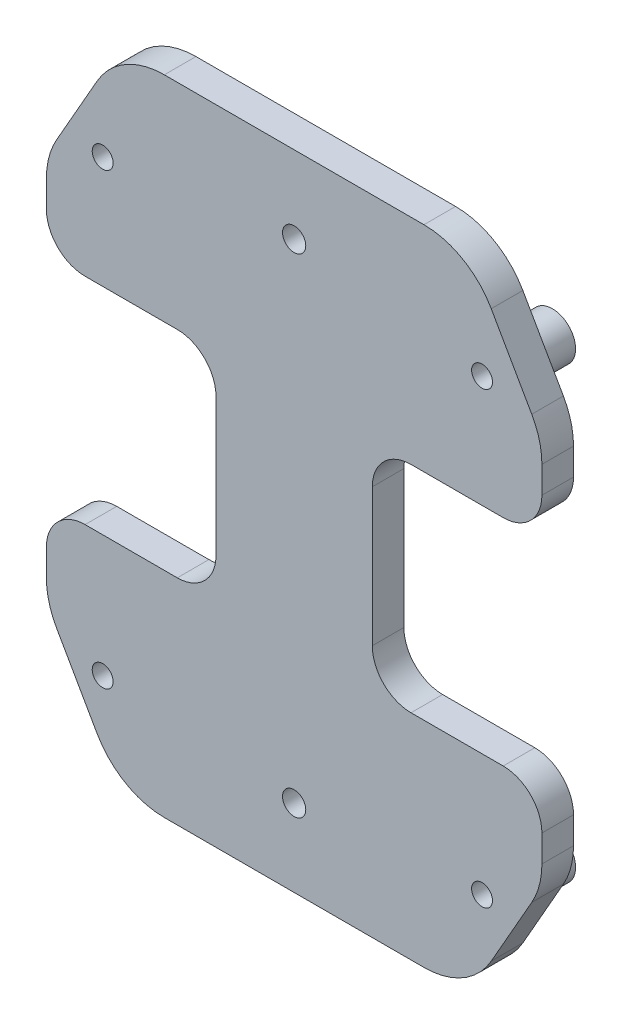
SolidWorks part; units mm, degrees
ref_plane "Ön Düzlem" through (0, 0, 0) normal (0, 0, 1) x (1, 0, 0)
ref_plane "Üst Düzlem" through (0, 0, 0) normal (0, 1, 0) x (1, 0, 0)
ref_plane "Sağ Düzlem" through (0, 0, 0) normal (1, 0, 0) x (0, 0, -1)
sketch "Çizim1" plane through (0, 0, 0) normal (0, 0, 1) x (1, 0, 0)
  line L12 (-26.9423, 14.7698) -> (-15.0365, 14.7698)
  line L13 (-46.9741, 0.8817) -> (-14.6226, 0.8817) construction
  line L14 (-25.3981, 37.3713) -> (-30.6317, 28.1828)
  line L15 (-31.9423, 23.2336) -> (-31.9423, 19.7698)
  line L16 (-26.9423, -13.0064) -> (-15.0365, -13.0064)
  line L17 (0.0577, 32.422) -> (0.0577, 69.5498) construction
  line L18 (-16.7087, 42.422) -> (16.8241, 42.422)
  line L19 (-16.7087, -40.6586) -> (16.8241, -40.6586)
  line L20 (-25.3981, -35.6078) -> (-30.6317, -26.4194)
  line L21 (25.5134, -35.6078) -> (30.747, -26.4194)
  line L22 (32.0577, 23.2336) -> (32.0577, 19.7698)
  line L23 (25.5134, 37.3713) -> (30.747, 28.1828)
  line L24 (27.0577, -13.0064) -> (15.1518, -13.0064)
  line L25 (27.0577, 14.7698) -> (15.1518, 14.7698)
  line L26 (-10.0365, 9.7698) -> (-10.0365, -8.0064)
  line L27 (10.1518, 9.7698) -> (10.1518, -8.0064)
  line L28 (32.0577, -18.0064) -> (32.0577, -21.4701)
  line L29 (-31.9423, -18.0064) -> (-31.9423, -21.4701)
  circle A0 centre (20.2843, 32.422) radius 1.5
  circle A1 centre (-20.1689, 32.422) radius 1.5
  circle A2 centre (-20.1689, -30.6586) radius 1.5
  circle A3 centre (20.2843, -30.6586) radius 1.5
  circle A16 centre (22.0577, -21.1183) radius 1.275
  circle A17 centre (-21.9423, -21.1183) radius 1.275
  circle A18 centre (22.0577, 22.8817) radius 1.275
  circle A19 centre (-21.9423, 22.8817) radius 1.275
  arc A20 (-30.6317, 28.1828) -> (-31.9423, 23.2336) centre (-21.9423, 23.2336) ccw
  arc A21 (-25.3981, 37.3713) -> (-16.7087, 42.422) centre (-16.7087, 32.422) cw
  arc A22 (-25.3981, -35.6078) -> (-16.7087, -40.6586) centre (-16.7087, -30.6586) ccw
  arc A23 (-30.6317, -26.4194) -> (-31.9423, -21.4701) centre (-21.9423, -21.4701) cw
  arc A24 (30.747, -26.4194) -> (32.0577, -21.4701) centre (22.0577, -21.4701) ccw
  arc A25 (25.5134, -35.6078) -> (16.8241, -40.6586) centre (16.8241, -30.6586) cw
  arc A26 (25.5134, 37.3713) -> (16.8241, 42.422) centre (16.8241, 32.422) ccw
  arc A27 (30.747, 28.1828) -> (32.0577, 23.2336) centre (22.0577, 23.2336) cw
  arc A28 (32.0577, -18.0064) -> (27.0577, -13.0064) centre (27.0577, -18.0064) ccw
  arc A29 (-26.9423, -13.0064) -> (-31.9423, -18.0064) centre (-26.9423, -18.0064) ccw
  arc A30 (15.1518, -13.0064) -> (10.1518, -8.0064) centre (15.1518, -8.0064) cw
  arc A31 (-10.0365, -8.0064) -> (-15.0365, -13.0064) centre (-15.0365, -8.0064) cw
  arc A32 (27.0577, 14.7698) -> (32.0577, 19.7698) centre (27.0577, 19.7698) ccw
  arc A33 (15.1518, 14.7698) -> (10.1518, 9.7698) centre (15.1518, 9.7698) ccw
  arc A34 (-15.0365, 14.7698) -> (-10.0365, 9.7698) centre (-15.0365, 9.7698) cw
  arc A35 (-31.9423, 19.7698) -> (-26.9423, 14.7698) centre (-26.9423, 19.7698) ccw
  circle A36 centre (0.0577, 32.422) radius 1.5
  circle A37 centre (0.0577, -30.6586) radius 1.5
  point P16 (32.0577, 0.8817)
  point P26 (0.0577, 42.422)
  point P27 (-31.9423, 0.8817)
  point P40 (0.0577, -40.6586)
  point P53 (32.0577, -13.0064)
  point P56 (-31.9423, -13.0064)
  point P64 (10.1518, -13.0064)
  point P67 (-10.0365, -13.0064)
  point P70 (32.0577, 14.7698)
  point P73 (10.1518, 14.7698)
  point P76 (-10.0365, 14.7698)
  point P79 (-31.9423, 14.7698)
  dimension "D1" = 10
  dimension "D2" = 5
extrude "Yükseklik-Ekstrüzyon1" add sketch "Çizim1" along normal blind 8
sketch "Çizim2" plane through (0, 0, 0) normal (0, 0, -1) x (-1, 0, 0)
  circle A0 centre (-22.0577, 22.8817) radius 4
  circle A1 centre (21.9423, 22.8817) radius 4
  circle A2 centre (-22.0577, -21.1183) radius 4
  circle A3 centre (21.9423, -21.1183) radius 4
  circle A4 centre (-0.0577, 32.422) radius 4
  circle A5 centre (-0.0577, -30.6586) radius 4
  dimension "D1" = 8
extrude "Kes-Ekstrüzyon1" cut sketch "Çizim2" against normal blind 5
sketch "Çizim3" plane through (0, 0, 8) normal (0, 0, 1) x (1, 0, 0)
  circle A0 centre (-20.1689, 32.422) radius 3.5
  circle A1 centre (20.2843, 32.422) radius 3.5
  circle A2 centre (20.2843, -30.6586) radius 3.5
  circle A3 centre (-20.1689, -30.6586) radius 3.5
  dimension "D1" = 7
extrude "Kes-Ekstrüzyon2" cut sketch "Çizim3" against normal blind 5
sketch "Çizim5" plane through (0, 0, 8) normal (0, 0, 1) x (1, 0, 0)
  line L0 (-10.0365, 0.8817) -> (-29.4082, 0.8817) construction
  line L1 (-5.8592, 35.2656) -> (5.9745, 35.2656)
  line L2 (-5.8592, 35.2656) -> (-5.8592, 29.5785)
  line L3 (-5.8592, 29.5785) -> (5.9745, 29.5785)
  line L4 (5.9745, 35.2656) -> (5.9745, 29.5785)
  line L5 (-5.8592, 35.2656) -> (5.9745, 29.5785) construction
  line L6 (-5.8592, 29.5785) -> (5.9745, 35.2656) construction
  line L7 (-10.0365, 9.7698) -> (-10.0365, -8.0064) construction
  line L8 (-5.8592, -27.815) -> (5.9745, -33.5021) construction
  line L9 (-5.8592, -33.5021) -> (5.9745, -27.815) construction
  line L10 (5.9745, -33.5021) -> (5.9745, -27.815)
  line L11 (-5.8592, -27.815) -> (5.9745, -27.815)
  line L12 (-5.8592, -33.5021) -> (-5.8592, -27.815)
  line L13 (-5.8592, -33.5021) -> (5.9745, -33.5021)
  point P0 (0.0577, 32.422)
  point P14 (0.0577, -30.6586)
extrude "Yükseklik-Ekstrüzyon2" add sketch "Çizim5" along normal blind 55
sketch "Çizim6" plane through (0, 0, 8) normal (0, 0, -1) x (-1, 0, 0)
  circle A0 centre (-0.0577, 32.422) radius 1.5 construction
  circle A1 centre (-0.0577, -30.6586) radius 1.5
  circle A2 centre (-0.0577, -30.6586) radius 1.5
  circle A3 centre (-0.0577, 32.422) radius 1.5
  dimension "D1" = 0
extrude "Kes-Ekstrüzyon3" cut sketch "Çizim6" against normal blind 70
sketch "Çizim7" plane through (0, 0, 63) normal (0, 0, 1) x (1, 0, 0)
  line L16 (-31.9423, 23.2336) -> (-31.9423, 19.7698)
  line L17 (-26.9423, 14.7698) -> (-15.0365, 14.7698)
  line L18 (-10.0365, 9.7698) -> (-10.0365, -8.0064)
  line L19 (-15.0365, -13.0064) -> (-26.9423, -13.0064)
  line L20 (-31.9423, -18.0064) -> (-31.9423, -21.4701)
  line L21 (-30.6317, -26.4194) -> (-25.3981, -35.6078)
  line L22 (-16.7087, -40.6586) -> (16.8241, -40.6586)
  line L23 (25.5134, -35.6078) -> (30.747, -26.4194)
  line L24 (32.0577, -21.4701) -> (32.0577, -18.0064)
  line L25 (27.0577, -13.0064) -> (15.1518, -13.0064)
  line L26 (10.1518, -8.0064) -> (10.1518, 9.7698)
  line L27 (15.1518, 14.7698) -> (27.0577, 14.7698)
  line L28 (32.0577, 19.7698) -> (32.0577, 23.2336)
  line L29 (30.747, 28.1828) -> (25.5134, 37.3713)
  line L30 (16.8241, 42.422) -> (-16.7087, 42.422)
  line L31 (-25.3981, 37.3713) -> (-30.6317, 28.1828)
  line L32 (-31.9423, 23.2336) -> (-31.9423, 19.7698)
  line L33 (-26.9423, 14.7698) -> (-15.0365, 14.7698)
  line L34 (-10.0365, 9.7698) -> (-10.0365, -8.0064)
  line L35 (-15.0365, -13.0064) -> (-26.9423, -13.0064)
  line L36 (-31.9423, -18.0064) -> (-31.9423, -21.4701)
  line L37 (-30.6317, -26.4194) -> (-25.3981, -35.6078)
  line L38 (-16.7087, -40.6586) -> (16.8241, -40.6586)
  line L39 (25.5134, -35.6078) -> (30.747, -26.4194)
  line L40 (32.0577, -21.4701) -> (32.0577, -18.0064)
  line L41 (27.0577, -13.0064) -> (15.1518, -13.0064)
  line L42 (10.1518, -8.0064) -> (10.1518, 9.7698)
  line L43 (15.1518, 14.7698) -> (27.0577, 14.7698)
  line L44 (32.0577, 19.7698) -> (32.0577, 23.2336)
  line L45 (30.747, 28.1828) -> (25.5134, 37.3713)
  line L46 (16.8241, 42.422) -> (-16.7087, 42.422)
  line L47 (-25.3981, 37.3713) -> (-30.6317, 28.1828)
  arc A16 (-30.6317, 28.1828) -> (-31.9423, 23.2336) centre (-21.9423, 23.2336) ccw
  arc A17 (-31.9423, 19.7698) -> (-26.9423, 14.7698) centre (-26.9423, 19.7698) ccw
  arc A18 (-10.0365, 9.7698) -> (-15.0365, 14.7698) centre (-15.0365, 9.7698) ccw
  arc A19 (-15.0365, -13.0064) -> (-10.0365, -8.0064) centre (-15.0365, -8.0064) ccw
  arc A20 (-26.9423, -13.0064) -> (-31.9423, -18.0064) centre (-26.9423, -18.0064) ccw
  arc A21 (-31.9423, -21.4701) -> (-30.6317, -26.4194) centre (-21.9423, -21.4701) ccw
  arc A22 (-25.3981, -35.6078) -> (-16.7087, -40.6586) centre (-16.7087, -30.6586) ccw
  arc A23 (16.8241, -40.6586) -> (25.5134, -35.6078) centre (16.8241, -30.6586) ccw
  arc A24 (30.747, -26.4194) -> (32.0577, -21.4701) centre (22.0577, -21.4701) ccw
  arc A25 (32.0577, -18.0064) -> (27.0577, -13.0064) centre (27.0577, -18.0064) ccw
  arc A26 (10.1518, -8.0064) -> (15.1518, -13.0064) centre (15.1518, -8.0064) ccw
  arc A27 (15.1518, 14.7698) -> (10.1518, 9.7698) centre (15.1518, 9.7698) ccw
  arc A28 (27.0577, 14.7698) -> (32.0577, 19.7698) centre (27.0577, 19.7698) ccw
  arc A29 (32.0577, 23.2336) -> (30.747, 28.1828) centre (22.0577, 23.2336) ccw
  arc A30 (25.5134, 37.3713) -> (16.8241, 42.422) centre (16.8241, 32.422) ccw
  arc A31 (-16.7087, 42.422) -> (-25.3981, 37.3713) centre (-16.7087, 32.422) ccw
  arc A32 (-30.6317, 28.1828) -> (-31.9423, 23.2336) centre (-21.9423, 23.2336) ccw
  arc A33 (-31.9423, 19.7698) -> (-26.9423, 14.7698) centre (-26.9423, 19.7698) ccw
  arc A34 (-10.0365, 9.7698) -> (-15.0365, 14.7698) centre (-15.0365, 9.7698) ccw
  arc A35 (-15.0365, -13.0064) -> (-10.0365, -8.0064) centre (-15.0365, -8.0064) ccw
  arc A36 (-26.9423, -13.0064) -> (-31.9423, -18.0064) centre (-26.9423, -18.0064) ccw
  arc A37 (-31.9423, -21.4701) -> (-30.6317, -26.4194) centre (-21.9423, -21.4701) ccw
  arc A38 (-25.3981, -35.6078) -> (-16.7087, -40.6586) centre (-16.7087, -30.6586) ccw
  arc A39 (16.8241, -40.6586) -> (25.5134, -35.6078) centre (16.8241, -30.6586) ccw
  arc A40 (30.747, -26.4194) -> (32.0577, -21.4701) centre (22.0577, -21.4701) ccw
  arc A41 (32.0577, -18.0064) -> (27.0577, -13.0064) centre (27.0577, -18.0064) ccw
  arc A42 (10.1518, -8.0064) -> (15.1518, -13.0064) centre (15.1518, -8.0064) ccw
  arc A43 (15.1518, 14.7698) -> (10.1518, 9.7698) centre (15.1518, 9.7698) ccw
  arc A44 (27.0577, 14.7698) -> (32.0577, 19.7698) centre (27.0577, 19.7698) ccw
  arc A45 (32.0577, 23.2336) -> (30.747, 28.1828) centre (22.0577, 23.2336) ccw
  arc A46 (25.5134, 37.3713) -> (16.8241, 42.422) centre (16.8241, 32.422) ccw
  arc A47 (-16.7087, 42.422) -> (-25.3981, 37.3713) centre (-16.7087, 32.422) ccw
  dimension "D1" = 0
extrude "Yükseklik-Ekstrüzyon3" add sketch "Çizim7" along normal blind 10
sketch "Çizim8" plane through (0, 0, 73) normal (0, 0, 1) x (1, 0, 0)
  circle A0 centre (0.0577, -30.6586) radius 1.5 construction
  circle A1 centre (0.0577, 32.422) radius 1.5 construction
  circle A2 centre (0.0577, -30.6586) radius 1.5
  circle A3 centre (0.0577, 32.422) radius 1.5
extrude "Kes-Ekstrüzyon4" cut sketch "Çizim8" against normal blind 10
sketch "Çizim9" plane through (0, 35.2656, 0) normal (0, 1, 0) x (1, 0, 0)
  line L1 (-52.9465, 12.3866) -> (44.8267, 12.3866)
  line L2 (-52.9465, 12.3866) -> (-52.9465, -68.9164)
  line L3 (-52.9465, -68.9164) -> (44.8267, -68.9164)
  line L4 (44.8267, 12.3866) -> (44.8267, -68.9164)
extrude "Kes-Ekstrüzyon5" cut sketch "Çizim9" against normal mid plane 189
sketch "Çizim10" plane through (0, 0, 68.9164) normal (0, 0, -1) x (-1, 0, 0)
  circle A0 centre (24.6732, -28.7639) radius 1.35
  circle A1 centre (24.6732, -28.7639) radius 3
  circle A2 centre (-24.3268, -28.7639) radius 1.35
  circle A3 centre (-24.3268, -28.7639) radius 3
  circle A4 centre (-24.3268, 29.2361) radius 1.35
  circle A5 centre (-24.3268, 29.2361) radius 3
  circle A6 centre (24.6732, 29.2361) radius 1.35
  circle A7 centre (24.6732, 29.2361) radius 3
extrude "Yükseklik-Ekstrüzyon4" add sketch "Çizim10" along normal blind 5
sketch "Çizim12" plane through (0, 0, 68.9164) normal (0, 0, -1) x (-1, 0, 0)
  circle A0 centre (-24.3268, -28.7639) radius 1.35 construction
  circle A1 centre (24.6732, -28.7639) radius 1.35 construction
  circle A2 centre (24.6732, 29.2361) radius 1.35 construction
  circle A3 centre (-24.3268, 29.2361) radius 1.35 construction
  circle A4 centre (-24.3268, -28.7639) radius 1.35
  circle A5 centre (24.6732, -28.7639) radius 1.35
  circle A6 centre (24.6732, 29.2361) radius 1.35
  circle A7 centre (-24.3268, 29.2361) radius 1.35
extrude "Kes-Ekstrüzyon6" cut sketch "Çizim12" against normal mid plane 23
